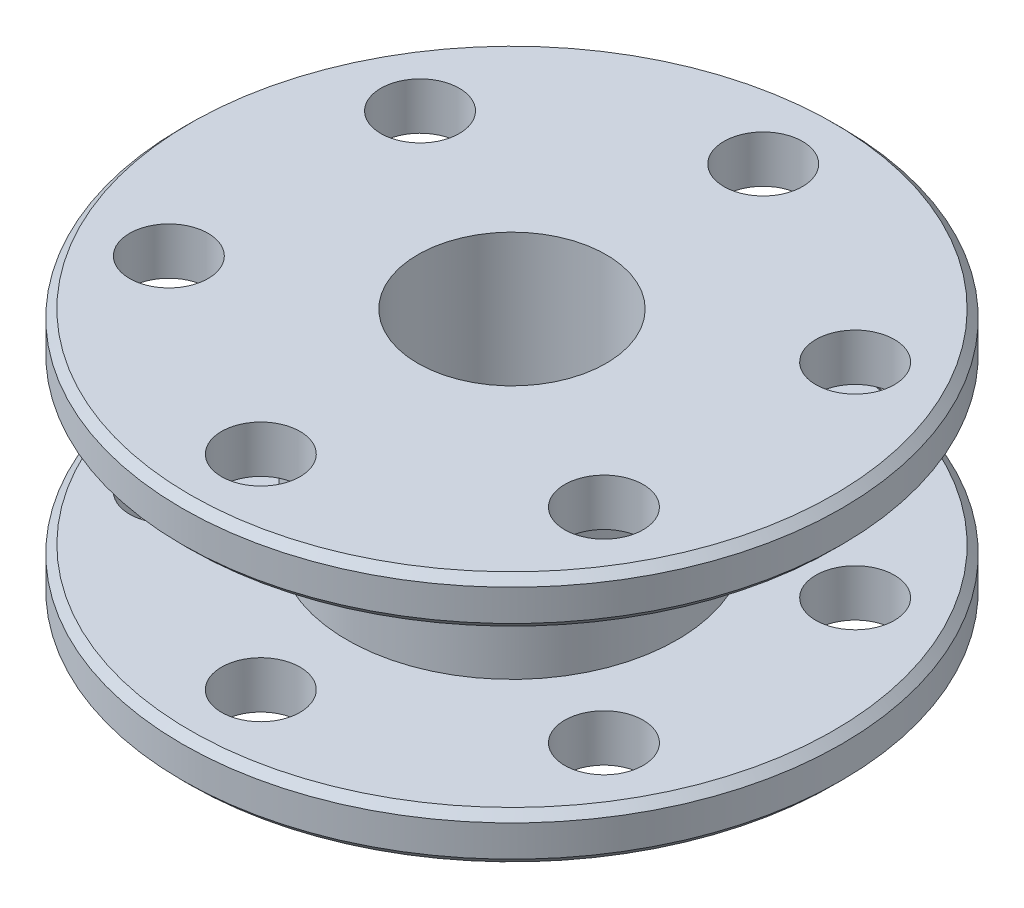
SolidWorks part; units mm, degrees
ref_plane "Front Plane" through (0, 0, 0) normal (0, 0, 1) x (1, 0, 0)
ref_plane "Top Plane" through (0, 0, 0) normal (0, 1, 0) x (1, 0, 0)
ref_plane "Right Plane" through (0, 0, 0) normal (1, 0, 0) x (0, 0, -1)
sketch "Sketch1" plane through (0, 0, 0) normal (0, 1, 0) x (1, 0, 0)
  circle A0 centre (0, 0) radius 21
  circle A1 centre (0, 0) radius 6
  circle A2 centre (0, 0) radius 16 construction
  circle A3 centre (0, 16) radius 2.5
  circle A4 centre (13.8564, 8) radius 2.5
  circle A5 centre (13.8564, -8) radius 2.5
  circle A6 centre (0, -16) radius 2.5
  circle A7 centre (-13.8564, -8) radius 2.5
  circle A8 centre (-13.8564, 8) radius 2.5
  point P19 (0, 0)
  dimension "D1" = 42
  dimension "D2" = 12
  dimension "D3" = 6
extrude "Boss-Extrude1" add sketch "Sketch1" along normal blind 16
sketch "Sketch2" plane through (0, 0, 0) normal (1, 0, 0) x (0, 0, -1)
  line L0 (0, 0) -> (0, 21.3184) construction
  line L1 (21, 16) -> (-21, 16) construction
  line L2 (10.5104, 13) -> (30.0668, 13)
  line L3 (10.5104, 13) -> (10.5104, 3)
  line L4 (10.5104, 3) -> (30.0668, 3)
  line L5 (30.0668, 13) -> (30.0668, 3)
  line L6 (-21, 0) -> (21, 0) construction
  dimension "D1" = 3
  dimension "D2" = 3
revolve "Cut-Revolve1" cut sketch "Sketch2" angle 360 about L0
chamfer "Chamfer1" distance 0.5 angle 45 2 edges at (0, 3, -21) (0, 13, 21)
chamfer "Chamfer2" distance 0.5 angle 45 2 edges at (0, 0, 21) (0, 16, 21)
